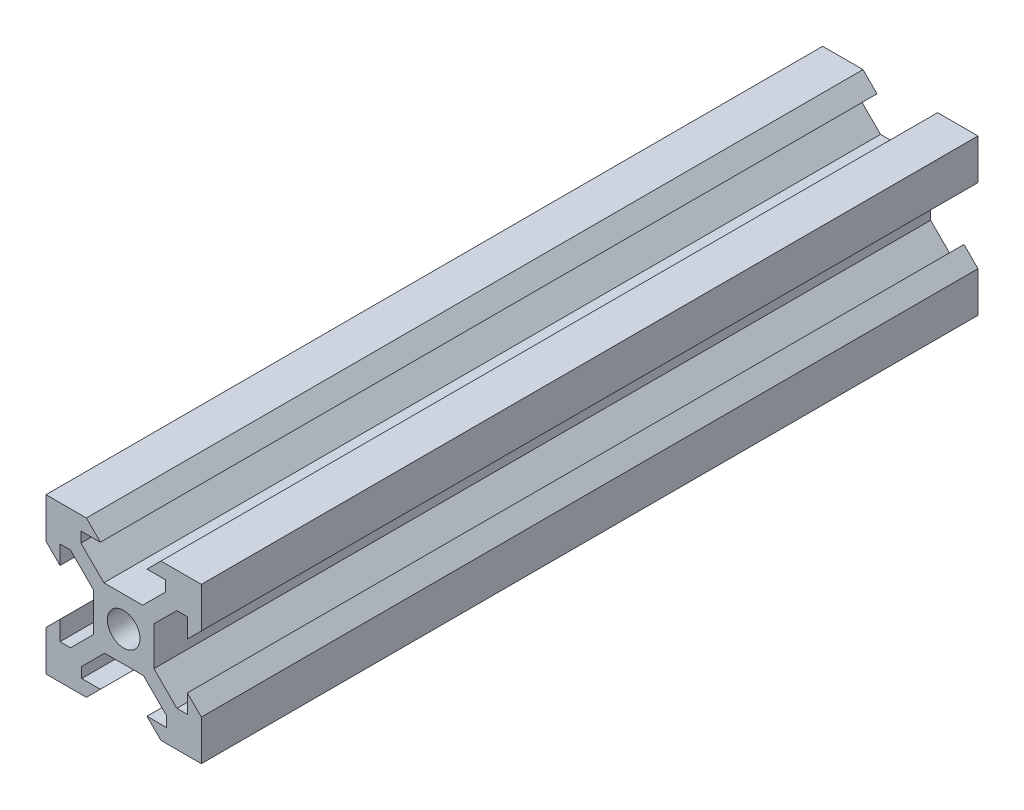
SolidWorks part; units mm, degrees
ref_plane "Alzado" through (0, 0, 0) normal (0, 0, 1) x (1, 0, 0)
ref_plane "Planta" through (0, 0, 0) normal (0, 1, 0) x (1, 0, 0)
ref_plane "Vista lateral" through (0, 0, 0) normal (1, 0, 0) x (0, 0, -1)
sketch "Croquis1" plane through (0, 0, 0) normal (0, 0, 1) x (1, 0, 0)
  line L0 (0, 20.9127) -> (0, 3.9) construction
  line L1 (-24.1207, 0) -> (-3.9, 0) construction
  line L2 (3, 8.2) -> (5.4, 8.2)
  line L3 (-10, 10) -> (-4.8, 10)
  line L4 (8.2, -3) -> (8.2, -5.4)
  line L5 (10, 10) -> (10, 4.8)
  line L6 (3.9, 2.55) -> (3.9, -2.45)
  line L7 (8.2, 5.5) -> (8.2, 3)
  line L8 (-2.55, 3.9) -> (2.45, 3.9)
  line L9 (8.2, 5.5) -> (6.85, 5.5)
  line L10 (8.2, -5.4) -> (6.85, -5.4)
  line L11 (8.2, -3) -> (10, -4.8)
  line L12 (-5.5, 8.2) -> (-3, 8.2)
  line L13 (-5.5, 8.2) -> (-5.5, 6.85)
  line L14 (10, -10) -> (10, -4.8)
  line L15 (5.4, 8.2) -> (5.4, 6.85)
  line L16 (3, 8.2) -> (4.8, 10)
  line L17 (10, 10) -> (4.8, 10)
  line L18 (8.2, 3) -> (10, 4.8)
  line L19 (6.85, 5.5) -> (3.9, 2.55)
  line L20 (6.85, -5.4) -> (3.9, -2.45)
  line L21 (20.9127, 0) -> (3.9, 0) construction
  line L22 (-3, -8.2) -> (-5.4, -8.2)
  line L23 (10, -10) -> (4.8, -10)
  line L24 (2.55, -3.9) -> (-2.45, -3.9)
  line L25 (5.5, -8.2) -> (3, -8.2)
  line L26 (5.5, -8.2) -> (5.5, -6.85)
  line L27 (-5.4, -8.2) -> (-5.4, -6.85)
  line L28 (-3, -8.2) -> (-4.8, -10)
  line L29 (-10, -10) -> (-4.8, -10)
  line L30 (3, -8.2) -> (4.8, -10)
  line L31 (5.5, -6.85) -> (2.55, -3.9)
  line L32 (-5.4, -6.85) -> (-2.45, -3.9)
  line L33 (0, -20.9127) -> (0, -3.9) construction
  line L34 (-8.2, 3) -> (-8.2, 5.4)
  line L35 (-10, -10) -> (-10, -4.8)
  line L36 (-3.9, -2.55) -> (-3.9, 2.45)
  line L37 (-8.2, -5.5) -> (-8.2, -3)
  line L38 (-8.2, -5.5) -> (-6.85, -5.5)
  line L39 (-8.2, 5.4) -> (-6.85, 5.4)
  line L40 (-3, 8.2) -> (-4.8, 10)
  line L41 (-8.2, 3) -> (-10, 4.8)
  line L42 (-5.5, 6.85) -> (-2.55, 3.9)
  line L43 (-10, 10) -> (-10, 4.8)
  line L44 (5.4, 6.85) -> (2.45, 3.9)
  line L45 (-8.2, -3) -> (-10, -4.8)
  line L46 (-6.85, -5.5) -> (-3.9, -2.55)
  line L47 (-6.85, 5.4) -> (-3.9, 2.45)
  line L48 (-20.9127, 0) -> (-3.9, 0) construction
  circle A0 centre (0, 0) radius 2.1
  point P45 (-0.05, 0.05)
  point P64 (0, 0)
  dimension "D5" = 4
  dimension "D1" = 45
  dimension "D2" = 45
  dimension "D3" = 6
  dimension "D4" = 3
  dimension "D6" = 8.2
extrude "Saliente-Extruir1" add sketch "Croquis1" along normal blind 100
